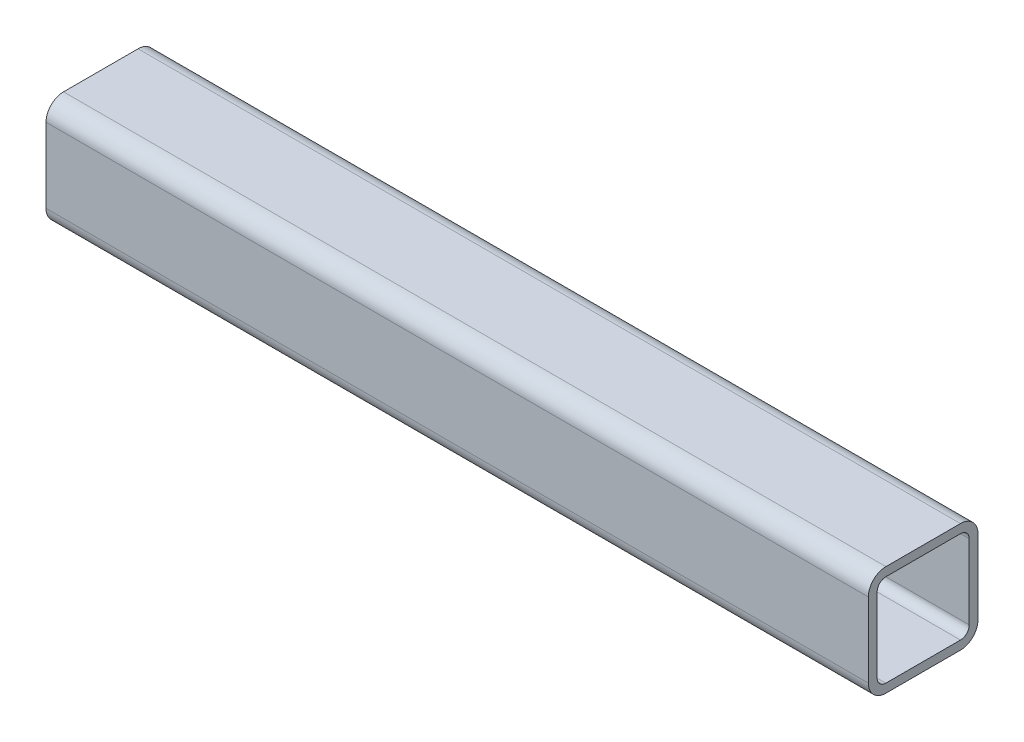
SolidWorks part; units mm, degrees
ref_plane "Front Plane" through (0, 0, 0) normal (0, 0, 1) x (1, 0, 0)
ref_plane "Top Plane" through (0, 0, 0) normal (0, 1, 0) x (1, 0, 0)
ref_plane "Right Plane" through (0, 0, 0) normal (1, 0, 0) x (0, 0, -1)
sketch "Sketch1" plane through (0, 0, 0) normal (0, 1, 0) x (1, 0, 0)
  line L0 (0, 0) -> (300, 0)
  dimension "D1" = 300
other "Tube (square) 40 X 40 X 3.2(6)"
ref_plane "Plane1" through (0, 0, 0) normal (1, 0, 0) x (0, 0, -1)
sketch "Sketch12" plane through (0, 0, 0) normal (1, 0, 0) x (0, 0, -1)
  line L0 (-13.6, -16.8) -> (13.6, -16.8)
  line L1 (-16.8, -13.6) -> (-16.8, 13.6)
  line L2 (13.6, 16.8) -> (-13.6, 16.8)
  line L3 (16.8, 13.6) -> (16.8, -13.6)
  line L4 (-13.6, -20) -> (13.6, -20)
  line L5 (-20, -13.6) -> (-20, 13.6)
  line L6 (13.6, 20) -> (-13.6, 20)
  line L7 (20, 13.6) -> (20, -13.6)
  line L8 (-20, 0) -> (-16.8, 0) construction
  line L9 (-16.8, 0) -> (16.8, 0) construction
  line L10 (16.8, 0) -> (20, 0) construction
  line L12 (0, 20) -> (0, 16.8) construction
  line L13 (0, 16.8) -> (0, -16.8) construction
  line L14 (0, -16.8) -> (0, -20) construction
  arc A0 (20, 13.6) -> (13.6, 20) centre (13.6, 13.6) ccw
  arc A1 (13.6, -20) -> (20, -13.6) centre (13.6, -13.6) ccw
  arc A2 (-20, -13.6) -> (-13.6, -20) centre (-13.6, -13.6) ccw
  arc A3 (-13.6, 20) -> (-20, 13.6) centre (-13.6, 13.6) ccw
  arc A4 (-13.6, 16.8) -> (-16.8, 13.6) centre (-13.6, 13.6) ccw
  arc A5 (16.8, 13.6) -> (13.6, 16.8) centre (13.6, 13.6) ccw
  arc A6 (13.6, -16.8) -> (16.8, -13.6) centre (13.6, -13.6) ccw
  arc A7 (-16.8, -13.6) -> (-13.6, -16.8) centre (-13.6, -13.6) ccw
  point P2 (-20, 20)
  point P33 (-20, -20)
  point P34 (20, -20)
  point P36 (20, 20)
  point P37 (0, 0)
  dimension "D1" = 6.4
  dimension "Thickness" = 3.2
  dimension "V_leg" = 40
  dimension "H_leg" = 40
